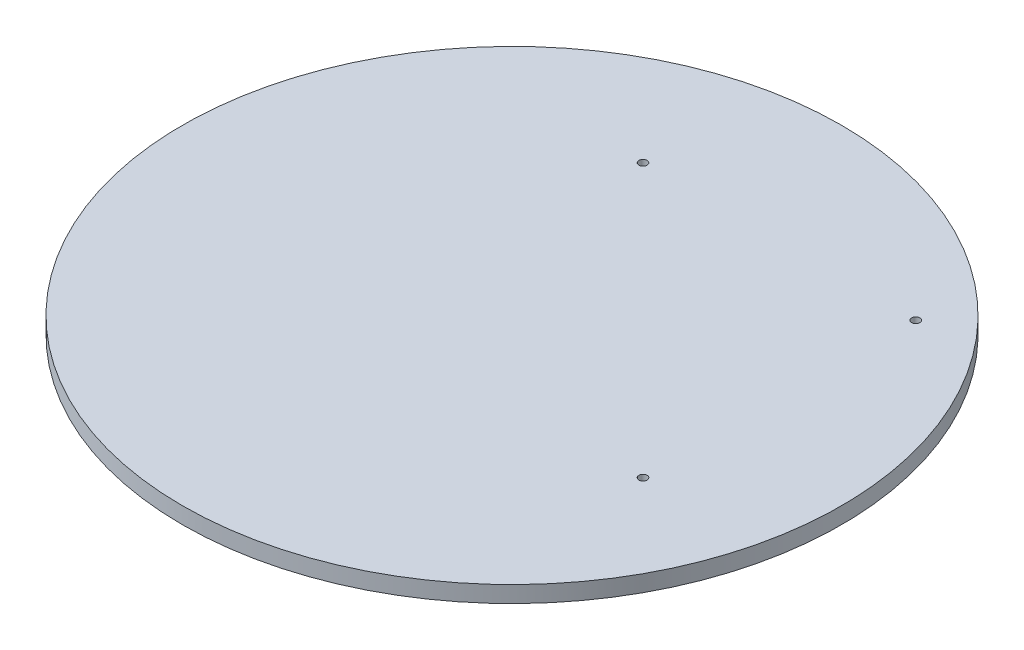
SolidWorks part; units mm, degrees
ref_plane "Front Plane" through (0, 0, 0) normal (0, 0, 1) x (1, 0, 0)
ref_plane "Top Plane" through (0, 0, 0) normal (0, 1, 0) x (1, 0, 0)
ref_plane "Right Plane" through (0, 0, 0) normal (1, 0, 0) x (0, 0, -1)
sketch "Sketch1" plane through (0, 0, 0) normal (0, 1, 0) x (1, 0, 0)
  circle A0 centre (0, 0) radius 200
  circle A1 centre (125, 120) radius 2.5
  circle A2 centre (-40.5, 120) radius 2.5
  circle A3 centre (125, -45.5) radius 2.5
  dimension "D1" = 165.5
  dimension "D3" = 5
  dimension "D4" = 400
  dimension "D5" = 125
  dimension "D2" = 165.5
  dimension "D6" = 120
extrude "Boss-Extrude1" add sketch "Sketch1" along normal blind 10 contours A0 | A2 | A1 | A3
